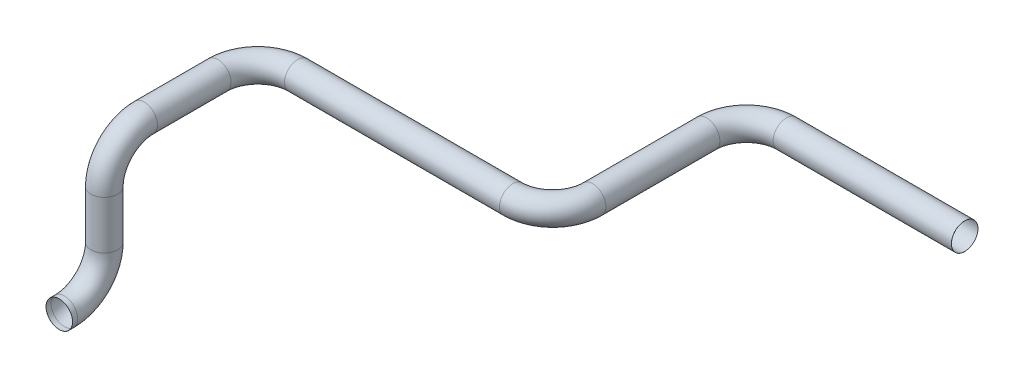
SolidWorks part; units mm, degrees
ref_plane "Front Plane" through (0, 0, 0) normal (0, 0, 1) x (1, 0, 0)
ref_plane "Top Plane" through (0, 0, 0) normal (0, 1, 0) x (1, 0, 0)
ref_plane "Right Plane" through (0, 0, 0) normal (1, 0, 0) x (0, 0, -1)
sketch3d "Croquis3D1"
  line L0 (0, 0, 0) -> (0, 0, -1.9142)
  line L1 (0, 15, -16.9142) -> (0, 33.1054, -16.9142)
  line L2 (0, 48.1054, -31.9142) -> (0, 48.1054, -59.601)
  line L3 (15, 48.1054, -74.601) -> (95.8233, 48.1054, -74.601)
  line L4 (110.8233, 48.1054, -89.601) -> (110.8233, 48.1054, -132.4221)
  line L5 (125.8233, 48.1054, -147.4221) -> (192.8161, 48.1054, -147.4221)
  arc A0 (0, 0, -1.9142) -> (0, 15, -16.9142) centre (0, 15, -1.9142) ccw
  arc A1 (0, 33.1054, -16.9142) -> (0, 48.1054, -31.9142) centre (0, 33.1054, -31.9142) ccw
  arc A2 (0, 48.1054, -59.601) -> (15, 48.1054, -74.601) centre (15, 48.1054, -59.601) ccw
  arc A3 (95.8233, 48.1054, -74.601) -> (110.8233, 48.1054, -89.601) centre (95.8233, 48.1054, -89.601) ccw
  arc A4 (110.8233, 48.1054, -132.4221) -> (125.8233, 48.1054, -147.4221) centre (125.8233, 48.1054, -132.4221) ccw
  point P10 (0, 0, -16.9142)
  point P11 (15, 15, -1.9142)
  point P14 (0, 48.1054, -16.9142)
  point P15 (-15, 33.1054, -31.9142)
  point P18 (0, 48.1054, -74.601)
  point P19 (15, 33.1054, -59.601)
  point P22 (110.8233, 48.1054, -74.601)
  point P23 (95.8233, 63.1054, -89.601)
  point P26 (110.8233, 48.1054, -147.4221)
  point P27 (125.8233, 33.1054, -132.4221)
  dimension "D1" = 15
sweep "Barrer2" add path "Croquis3D1" circular profile diameter 10 parameters "D3"=10
shell "Vaciado2" thickness 0.01
